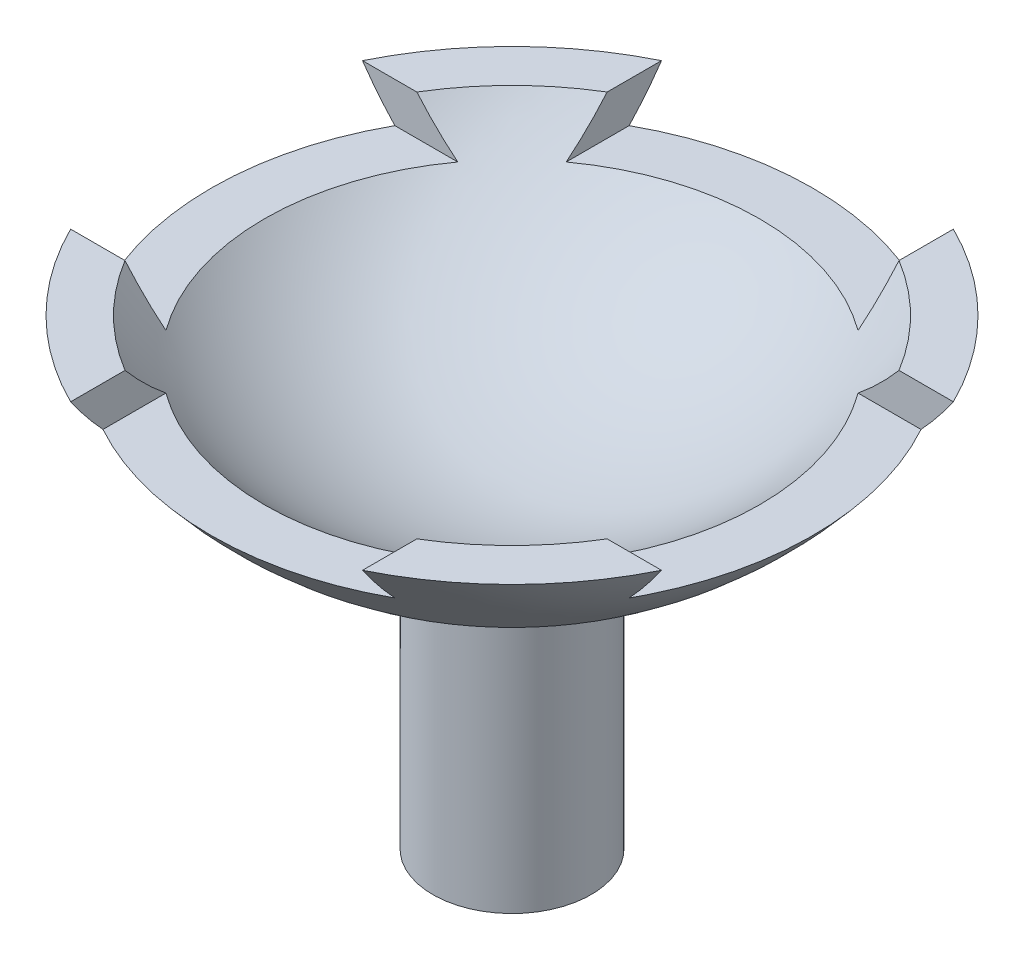
SolidWorks part; units mm, degrees
ref_plane "Front Plane" through (0, 0, 0) normal (0, 0, 1) x (1, 0, 0)
ref_plane "Top Plane" through (0, 0, 0) normal (0, 1, 0) x (1, 0, 0)
ref_plane "Right Plane" through (0, 0, 0) normal (1, 0, 0) x (0, 0, -1)
sketch "Sketch3" plane through (0, 0, 0) normal (0, 0, 1) x (1, 0, 0)
  line L2 (21.3481, 35) -> (24.9628, 35)
  line L3 (6, 21.75) -> (6, 0)
  line L4 (6, 0) -> (0, 0)
  line L5 (0, 24.1312) -> (0, 0)
  arc A0 (6, 21.75) -> (24.9628, 35) centre (0, 50.5312) ccw
  arc A1 (0, 24.1312) -> (21.3481, 35) centre (0, 50.5312) ccw
  arc A3 (0, 21.1312) -> (25.9136, 36.6443) centre (0, 50.5312) ccw construction
  arc A4 (0, 24.1312) -> (23.2693, 38.0613) centre (0, 50.5312) ccw construction
  point P6 (0, 26.2754)
  point P13 (0, 20.1136)
  dimension "D2" = 29.4
  dimension "D3" = 6
  dimension "D4" = 35
  dimension "D5" = 21.75
  dimension "D1" = 3
revolve "Revolve1" add sketch "Sketch3" angle 360 about L5
sketch "Sketch4" plane through (0, 0, 0) normal (0, 0, 1) x (1, 0, 0)
  line L0 (21.3481, 35) -> (-21.3481, 35) construction
  line L1 (-11.055, 35) -> (11.055, 35)
  line L2 (-11.055, 35) -> (-11.055, 31.96)
  line L3 (-11.055, 31.96) -> (11.055, 31.96)
  line L4 (11.055, 35) -> (11.055, 31.96)
  line L5 (0, 0) -> (0, 21.75) construction
  line L6 (-6, 21.75) -> (6, 21.75) construction
  dimension "D1" = 22.11
  dimension "D2" = 3.04
extrude "Cut-Extrude1" cut sketch "Sketch4" against normal up to next
pattern_circular "CirPattern2" count 4 over 360 about axis through (0, 0, 0) along (0, 1, 0) of "Cut-Extrude1"
fillet "Fillet1" radius 1.5 1 edges at (-6, 21.75, 0)
